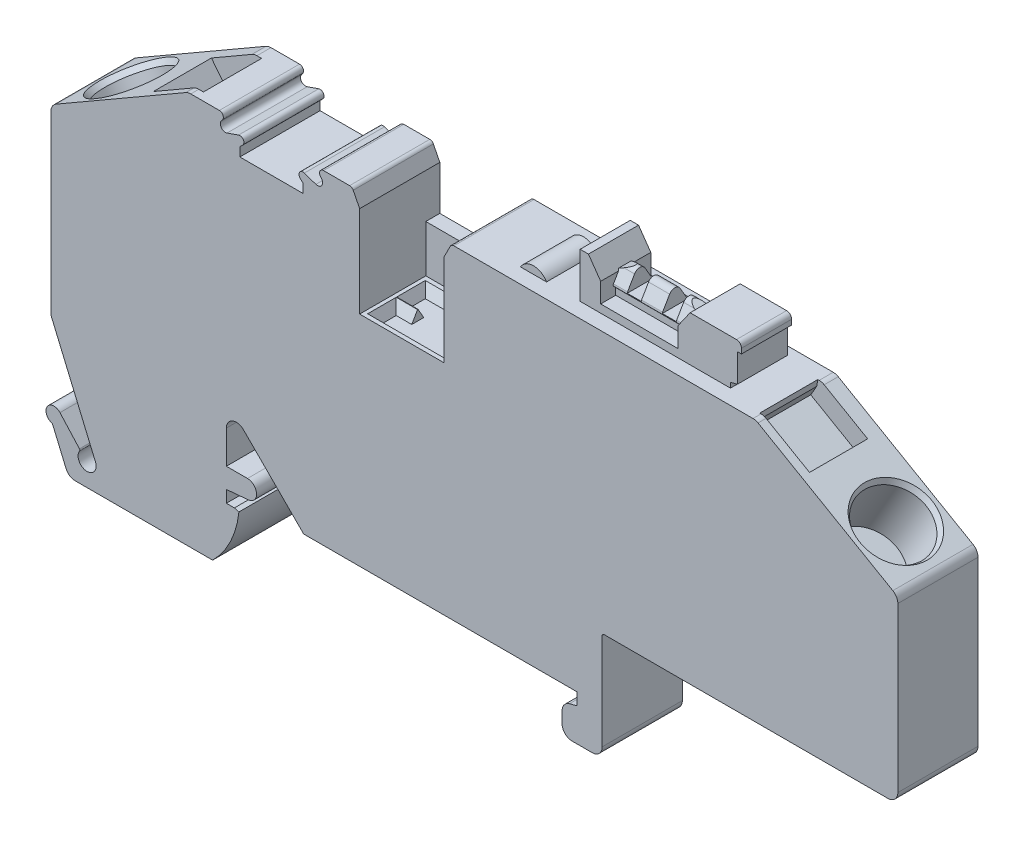
SolidWorks part; units mm, degrees
ref_plane "Front Plane" through (0, 0, 0) normal (0, 0, 1) x (1, 0, 0)
ref_plane "Top Plane" through (0, 0, 0) normal (0, 1, 0) x (1, 0, 0)
ref_plane "Right Plane" through (0, 0, 0) normal (1, 0, 0) x (0, 0, -1)
ref_plane "Plane1" through (0, 0, 0) normal (0, 0, 1) x (1, 0, 0)
sketch "Sketch1" plane through (0, 0, 0) normal (0, 0, 1) x (1, 0, 0)
  line L0 (-34.8241, -3.0721) -> (-33.5003, -6.1907)
  line L1 (-32.5798, -6.8) -> (-18.8723, -6.8)
  line L2 (-16.2473, -1.3213) -> (-16.7, -1.2)
  line L3 (-16.7, -1.2) -> (-17.5, -1.2)
  line L4 (-17.5, -1.2) -> (-17.5, 0)
  line L5 (-17.5, 0) -> (-15.3117, 0.1914)
  line L6 (-15.3907, 2) -> (-17.5, 2)
  line L7 (-17.5, 2) -> (-17.5, 5.3)
  line L8 (-15.7929, 6.0071) -> (-9.7858, 0)
  line L9 (-9.7858, 0) -> (17.5, 0)
  line L10 (17.5, 0) -> (17.5, -1.2)
  line L11 (17.5, -1.2) -> (16.7412, -1.4033)
  line L12 (16, -2.3693) -> (16, -3.5)
  line L13 (17, -4.5) -> (19, -4.5)
  line L14 (20, -3.5) -> (20, 6.1)
  line L15 (20.2, 6.3) -> (48.5, 6.3)
  line L16 (49.5, 7.3) -> (49.5, 23.6357)
  line L17 (49, 24.5017) -> (35.5518, 32.266)
  line L18 (35.0518, 32.4) -> (5.2, 32.4)
  line L19 (4.8431, 32.1806) -> (4.2, 30.9094)
  line L20 (4.2, 30.9094) -> (4.2, 21.8)
  line L21 (4.2, 21.8) -> (-4.2, 21.8)
  line L22 (-4.2, 21.8) -> (-4.2, 30.9094)
  line L23 (-4.2, 30.9094) -> (-4.8431, 32.1806)
  line L24 (-5.2, 32.4) -> (-7.8, 32.4)
  line L25 (-8.12, 31.76) -> (-8, 31.6)
  line L26 (-8.5637, 30.8276) -> (-9.719, 31.2279)
  line L27 (-10.1328, 30.5672) -> (-9.85, 30.2843)
  line L28 (-9.85, 30.2843) -> (-9.85, 29.4)
  line L29 (-9.85, 29.4) -> (-13, 29.4)
  line L30 (-13, 29.4) -> (-16.15, 29.4)
  line L31 (-16.15, 29.4) -> (-16.15, 30.2843)
  line L32 (-16.15, 30.2843) -> (-15.8672, 30.5672)
  line L33 (-16.281, 31.2279) -> (-17.4363, 30.8276)
  line L34 (-18, 31.6) -> (-17.88, 31.76)
  line L35 (-18.2, 32.4) -> (-21.0518, 32.4)
  line L36 (-21.5518, 32.266) -> (-34.5, 24.7904)
  line L37 (-35, 23.9244) -> (-35, 6.3)
  line L38 (-35, 6.3) -> (-30.5649, -4.1483)
  line L39 (-32.1591, -3.8225) -> (-34.102, -1.6647)
  arc A0 (-34.102, -1.6647) -> (-34.9458, -2.9602) centre (-34.6966, -2.2) ccw
  arc A1 (-34.9458, -2.9602) -> (-34.8241, -3.0721) centre (-35.0082, -3.1502) cw
  arc A2 (-33.5003, -6.1907) -> (-32.5798, -6.8) centre (-32.5798, -5.8) ccw
  arc A3 (-18.8723, -6.8) -> (-16.2473, -1.3213) centre (-25.2, -0.4) ccw
  arc A4 (-15.3117, 0.1914) -> (-15.3907, 2) centre (-15.3907, 1.094) ccw
  arc A5 (-17.5, 5.3) -> (-15.7929, 6.0071) centre (-16.5, 5.3) cw
  arc A6 (16.7412, -1.4033) -> (16, -2.3693) centre (17, -2.3693) ccw
  arc A7 (16, -3.5) -> (17, -4.5) centre (17, -3.5) ccw
  arc A8 (19, -4.5) -> (20, -3.5) centre (19, -3.5) ccw
  arc A9 (20, 6.1) -> (20.2, 6.3) centre (20.2, 6.1) cw
  arc A10 (48.5, 6.3) -> (49.5, 7.3) centre (48.5, 7.3) ccw
  arc A11 (49.5, 23.6357) -> (49, 24.5017) centre (48.5, 23.6357) ccw
  arc A12 (35.5518, 32.266) -> (35.0518, 32.4) centre (35.0518, 31.4) ccw
  arc A13 (5.2, 32.4) -> (4.8431, 32.1806) centre (5.2, 32) ccw
  arc A14 (-4.8431, 32.1806) -> (-5.2, 32.4) centre (-5.2, 32) ccw
  arc A15 (-7.8, 32.4) -> (-8.12, 31.76) centre (-7.8, 32) ccw
  arc A16 (-8, 31.6) -> (-8.5637, 30.8276) centre (-8.4, 31.3) cw
  arc A17 (-9.719, 31.2279) -> (-10.1328, 30.5672) centre (-9.85, 30.85) ccw
  arc A18 (-15.8672, 30.5672) -> (-16.281, 31.2279) centre (-16.15, 30.85) ccw
  arc A19 (-17.4363, 30.8276) -> (-18, 31.6) centre (-17.6, 31.3) cw
  arc A20 (-17.88, 31.76) -> (-18.2, 32.4) centre (-18.2, 32) ccw
  arc A21 (-21.0518, 32.4) -> (-21.5518, 32.266) centre (-21.0518, 31.4) ccw
  arc A22 (-34.5, 24.7904) -> (-35, 23.9244) centre (-34, 23.9244) ccw
  arc A23 (-30.5649, -4.1483) -> (-32.1453, -4.0053) centre (-31.3934, -4.5) cw
  arc A24 (-32.1453, -4.0053) -> (-32.1591, -3.8225) centre (-32.2706, -3.9229) ccw
extrude "Extrude1" add sketch "Sketch1" along normal blind 8
ref_plane "Plane2" through (0, 0, 0) normal (0, 0, 1) x (1, 0, 0)
sketch "Sketch2" plane through (0, 0, 0) normal (0, 0, 1) x (1, 0, 0)
  line L0 (-4.2, 21.8) -> (4.2, 21.8)
  line L1 (4.2, 21.8) -> (4.2, 26.5)
  line L2 (4.2, 26.5) -> (-4.2, 26.5)
  line L3 (-4.2, 26.5) -> (-4.2, 21.8)
extrude "Extrude2" add sketch "Sketch2" along normal blind 1.4
ref_plane "Plane3" through (0, 0, 0) normal (1, 0, 0) x (0, 0, -1)
sketch "Sketch3" plane through (0, 0, 0) normal (1, 0, 0) x (0, 0, -1)
  line L0 (-7.5774, 21.8) -> (-7, 20.8)
  line L1 (-7, 20.8) -> (-5.3, 20.8)
  line L2 (-5.3, 20.8) -> (-4.7226, 21.8)
  line L3 (-4.7226, 21.8) -> (-7.5774, 21.8)
extrude "Extrude3" cut sketch "Sketch3" against normal blind 4.2 and the other way blind 4.2
ref_plane "Plane4" through (0, 0, 0) normal (1, 0, 0) x (0, 0, -1)
sketch "Sketch4" plane through (0, 0, 0) normal (1, 0, 0) x (0, 0, -1)
  line L0 (-4.6774, 21.8) -> (-4.1, 20.8)
  line L1 (-4.1, 20.8) -> (-2.4, 20.8)
  line L2 (-2.4, 20.8) -> (-1.8226, 21.8)
  line L3 (-1.8226, 21.8) -> (-4.6774, 21.8)
extrude "Extrude4" cut sketch "Sketch4" against normal blind 4.2 and the other way blind 4.2
ref_plane "Plane5" through (0, 0, 0) normal (1, 0, 0) x (0, 0, -1)
sketch "Sketch5" plane through (0, 0, 0) normal (1, 0, 0) x (0, 0, -1)
  line L0 (-5.7, 21.8) -> (-5.7, 20.8)
  line L1 (-5.7, 20.8) -> (-3.7, 20.8)
  line L2 (-3.7, 20.8) -> (-3.7, 21.8)
  line L3 (-3.7, 21.8) -> (-5.7, 21.8)
extrude "Extrude5" cut sketch "Sketch5" against normal blind 1.7 and the other way blind 1.7
ref_plane "Plane6" through (0, 0, 0) normal (0, 0, 1) x (1, 0, 0)
sketch "Sketch6" plane through (0, 0, 0) normal (0, 0, 1) x (1, 0, 0)
  line L0 (3.25, 20.8) -> (4.2, 20.8)
  line L1 (4.2, 20.8) -> (4.2, 21.8)
  line L2 (4.2, 21.8) -> (3.8274, 21.8)
  line L3 (3.8274, 21.8) -> (3.25, 20.8)
extrude "Extrude6" add sketch "Sketch6" along normal blind 8
ref_plane "Plane7" through (0, 0, 0) normal (0, 0, 1) x (1, 0, 0)
sketch "Sketch7" plane through (0, 0, 0) normal (0, 0, 1) x (1, 0, 0)
  line L0 (-4.2, 21.8) -> (-4.2, 20.8)
  line L1 (-4.2, 20.8) -> (-3.25, 20.8)
  line L2 (-3.25, 20.8) -> (-3.8274, 21.8)
  line L3 (-3.8274, 21.8) -> (-4.2, 21.8)
extrude "Extrude7" add sketch "Sketch7" along normal blind 8
ref_plane "Plane8" through (0, 0, 4) normal (0, 0, 1) x (1, 0, 0)
sketch "Sketch8" plane through (0, 0, 4) normal (0, 0, 1) x (1, 0, 0)
  line L0 (42.1271, 21.1374) -> (39.2693, 22.7874)
  line L1 (39.2693, 22.7874) -> (42.1845, 27.8367)
  line L2 (42.1845, 27.8367) -> (42.1845, 28.4367)
  line L3 (42.1845, 28.4367) -> (45.3021, 26.6367)
  line L4 (45.3021, 26.6367) -> (42.1271, 21.1374)
  line L5 (45.3021, 26.6367) -> (42.1271, 21.1374) construction
  dimension "D1" = 6.35
revolve "Cut-Revolve1" cut sketch "Sketch8" angle 360 about L5
ref_plane "Plane9" through (0, 0, 4) normal (0, 0, 1) x (1, 0, 0)
sketch "Sketch9" plane through (0, 0, 4) normal (0, 0, 1) x (1, 0, 0)
  line L0 (-31.0021, 26.8099) -> (-27.8845, 28.6099)
  line L1 (-27.8845, 28.6099) -> (-27.8845, 28.0099)
  line L2 (-27.8845, 28.0099) -> (-24.9693, 22.9606)
  line L3 (-24.9693, 22.9606) -> (-27.8271, 21.3106)
  line L4 (-27.8271, 21.3106) -> (-31.0021, 26.8099)
  line L5 (-27.8271, 21.3106) -> (-31.0021, 26.8099) construction
  dimension "D1" = 6.35
revolve "Cut-Revolve2" cut sketch "Sketch9" angle 360 about L5
ref_plane "Plane10" through (0, 0, 1.4) normal (0, 0, 1) x (1, 0, 0)
sketch "Sketch10" plane through (0, 0, 1.4) normal (0, 0, 1) x (1, 0, 0)
  line L0 (34.213, 30.7296) -> (38.6461, 28.1702)
  line L1 (38.6461, 28.1702) -> (39.8895, 29.7617)
  line L2 (39.8895, 29.7617) -> (34.9531, 32.6117)
  line L3 (34.9531, 32.6117) -> (34.8008, 31.7478)
  line L4 (34.8008, 31.7478) -> (34.213, 30.7296)
extrude "Extrude8" cut sketch "Sketch10" along normal blind 5.8
ref_plane "Plane11" through (0, 0, 1.4) normal (0, 0, 1) x (1, 0, 0)
sketch "Sketch11" plane through (0, 0, 1.4) normal (0, 0, 1) x (1, 0, 0)
  line L0 (-25.5895, 29.9349) -> (-24.3461, 28.3434)
  line L1 (-24.3461, 28.3434) -> (-19.913, 30.9028)
  line L2 (-19.913, 30.9028) -> (-20.5008, 31.9211)
  line L3 (-20.5008, 31.9211) -> (-20.6531, 32.7849)
  line L4 (-20.6531, 32.7849) -> (-25.5895, 29.9349)
extrude "Extrude9" cut sketch "Sketch11" along normal blind 5.8
ref_plane "Plane12" through (0, 0, 4) normal (0, 0, 1) x (1, 0, 0)
sketch "Sketch12" plane through (0, 0, 4) normal (0, 0, 1) x (1, 0, 0)
  line L0 (10.15, 31.65) -> (31.3, 31.65)
  line L1 (31.3, 31.65) -> (31.3, 32.9)
  line L2 (31.3, 32.9) -> (32, 33.0876)
  line L3 (32, 33.0876) -> (32, 35.9)
  line L4 (32, 35.9) -> (32.4, 35.9)
  line L5 (32.4, 35.9) -> (32.4, 36.4)
  line L6 (31.9, 36.9) -> (27.2703, 36.9)
  line L7 (27.2703, 36.9) -> (26.05, 35.1572)
  line L8 (26.05, 35.1572) -> (26.05, 33.2)
  line L9 (26.05, 33.2) -> (18.35, 33.2)
  line L10 (18.35, 33.2) -> (18.35, 35.1572)
  line L11 (18.35, 35.1572) -> (17.1297, 36.9)
  line L12 (17.1297, 36.9) -> (16.3, 36.9)
  line L13 (16.3, 36.9) -> (16.3, 32.4)
  line L14 (16.3, 32.4) -> (12.949, 32.4)
  arc A0 (32.4, 36.4) -> (31.9, 36.9) centre (31.9, 36.4) ccw
  arc A1 (12.949, 32.4) -> (10.15, 31.65) centre (11.65, 31.65) ccw
extrude "Extrude10" add sketch "Sketch12" against normal blind 2.5 and the other way blind 2.5
ref_plane "Plane13" through (22.2, 0, 0) normal (1, 0, 0) x (0, 0, -1)
sketch "Sketch13" plane through (22.2, 0, 0) normal (1, 0, 0) x (0, 0, -1)
  line L0 (-5.15, 34.0268) -> (-5, 33.9402)
  line L1 (-5, 33.9402) -> (-5, 33.2)
  line L2 (-5, 33.2) -> (-3, 33.2)
  line L3 (-3, 33.2) -> (-3, 33.9402)
  line L4 (-3, 33.9402) -> (-2.85, 34.0268)
  line L5 (-2.7775, 34.3012) -> (-3.4824, 35.5035)
  line L6 (-4.5176, 35.5035) -> (-5.2225, 34.3012)
  arc A0 (-5.2225, 34.3012) -> (-5.15, 34.0268) centre (-5.05, 34.2) ccw
  arc A1 (-2.85, 34.0268) -> (-2.7775, 34.3012) centre (-2.95, 34.2) ccw
  arc A2 (-3.4824, 35.5035) -> (-4.5176, 35.5035) centre (-4, 35.2) ccw
extrude "Extrude11" add sketch "Sketch13" against normal blind 5 and the other way blind 5
ref_plane "Plane14" through (0, 0, 4) normal (0, 0, 1) x (1, 0, 0)
sketch "Sketch14" plane through (0, 0, 4) normal (0, 0, 1) x (1, 0, 0)
  line L0 (17.1297, 36.9) -> (18.25, 35.3)
  line L1 (18.25, 35.3) -> (19.3223, 35.8)
  line L2 (19.3223, 35.8) -> (19.75, 35.8)
  line L3 (19.75, 35.8) -> (19.75, 34.2)
  line L4 (19.75, 34.2) -> (21.15, 34.2)
  line L5 (21.15, 34.2) -> (21.15, 35.8)
  line L6 (21.15, 35.8) -> (23.25, 35.8)
  line L7 (23.25, 35.8) -> (23.25, 34.2)
  line L8 (23.25, 34.2) -> (24.65, 34.2)
  line L9 (24.65, 34.2) -> (24.65, 35.8)
  line L10 (24.65, 35.8) -> (25.0777, 35.8)
  line L11 (25.0777, 35.8) -> (26.15, 35.3)
  line L12 (26.15, 35.3) -> (27.2703, 36.9)
  line L13 (27.2703, 36.9) -> (22.2, 36.9)
  line L14 (22.2, 36.9) -> (17.1297, 36.9)
extrude "Extrude12" cut sketch "Sketch14" against normal blind 1.5 and the other way blind 1.5
